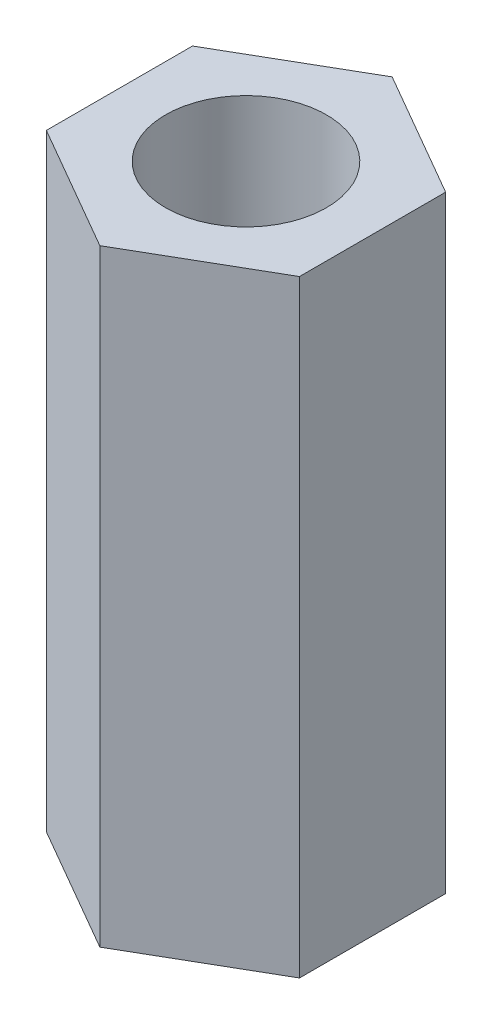
SolidWorks part; units mm, degrees
ref_plane "Front Plane" through (0, 0, 0) normal (0, 0, 1) x (1, 0, 0)
ref_plane "Top Plane" through (0, 0, 0) normal (0, 1, 0) x (1, 0, 0)
ref_plane "Right Plane" through (0, 0, 0) normal (1, 0, 0) x (0, 0, -1)
sketch "Sketch1" plane through (0, 0, 0) normal (0, 1, 0) x (1, 0, 0)
  line L0 (0, 2.887) -> (2.5002, 1.4435)
  line L1 (2.5002, 1.4435) -> (2.5002, -1.4435)
  line L2 (2.5002, -1.4435) -> (0, -2.887)
  line L3 (0, -2.887) -> (-2.5002, -1.4435)
  line L4 (-2.5002, -1.4435) -> (-2.5002, 1.4435)
  line L5 (-2.5002, 1.4435) -> (0, 2.887)
  circle A0 centre (0, 0) radius 1.59
  dimension "D2" = 3.18
  dimension "D3" = 2.887
extrude "Boss-Extrude1" add sketch "Sketch1" along normal blind 12
